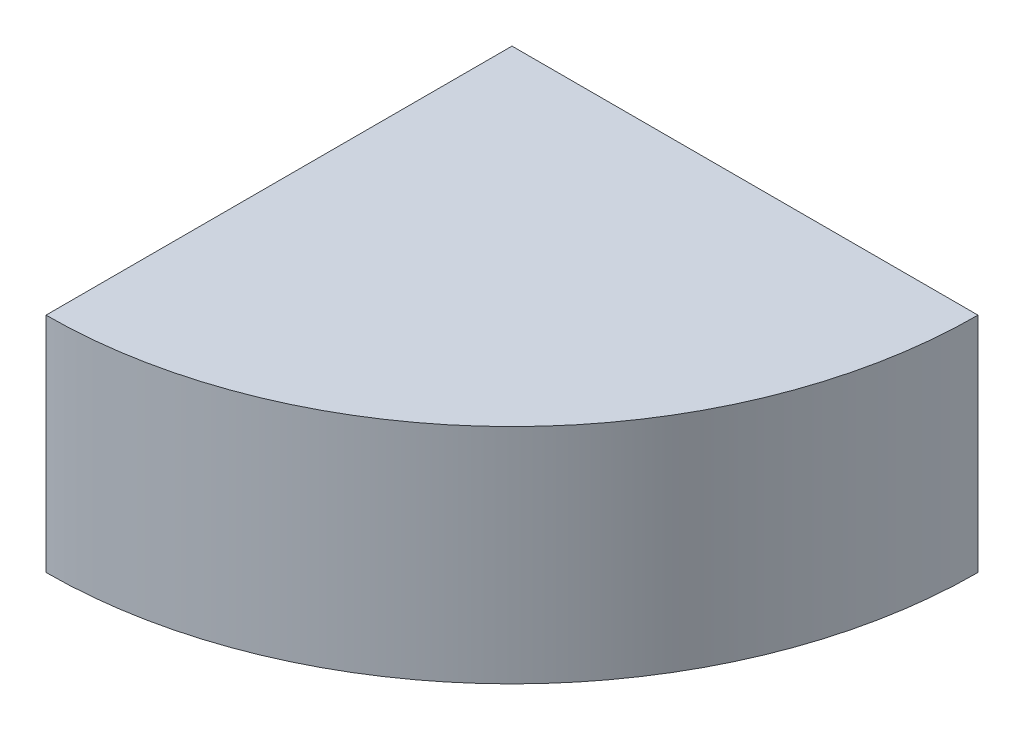
SolidWorks part; units mm, degrees
ref_plane "前视基准面" through (0, 0, 0) normal (0, 0, 1) x (1, 0, 0)
ref_plane "上视基准面" through (0, 0, 0) normal (0, 1, 0) x (1, 0, 0)
ref_plane "右视基准面" through (0, 0, 0) normal (1, 0, 0) x (0, 0, -1)
other "Configuration Table"
sketch "草图1" plane through (0, 0, 0) normal (0, 0, 1) x (1, 0, 0)
  line L1 (-115, 55) -> (115, 55)
  line L2 (-115, 55) -> (-115, -55)
  line L3 (-115, -55) -> (115, -55)
  line L4 (115, 55) -> (115, -55)
  line L5 (-115, 55) -> (115, -55) construction
  line L6 (-115, -55) -> (115, 55) construction
  circle A0 centre (-105, 45) radius 3
  circle A1 centre (-105, -45) radius 3
  circle A2 centre (105, -45) radius 3
  circle A3 centre (105, 45) radius 3
  point P0 (0, 0)
  point P16 (-102.2147, 56.7466)
  point P17 (-102.9781, -51.558)
  point P18 (-103.6235, -46.0533)
  dimension "D5" = 6
  dimension "D6" = 6
  dimension "D9" = 6
  dimension "D12" = 6
  dimension "D1" = 230
  dimension "D2" = 110
  dimension "D3" = 10
  dimension "D4" = 10
  dimension "D7" = 10
  dimension "D8" = 10
  dimension "D10" = 10
  dimension "D11" = 10
  dimension "D13" = 10
  dimension "D14" = 10
revolve "旋转1" add sketch "草图1" angle 90 about L2
